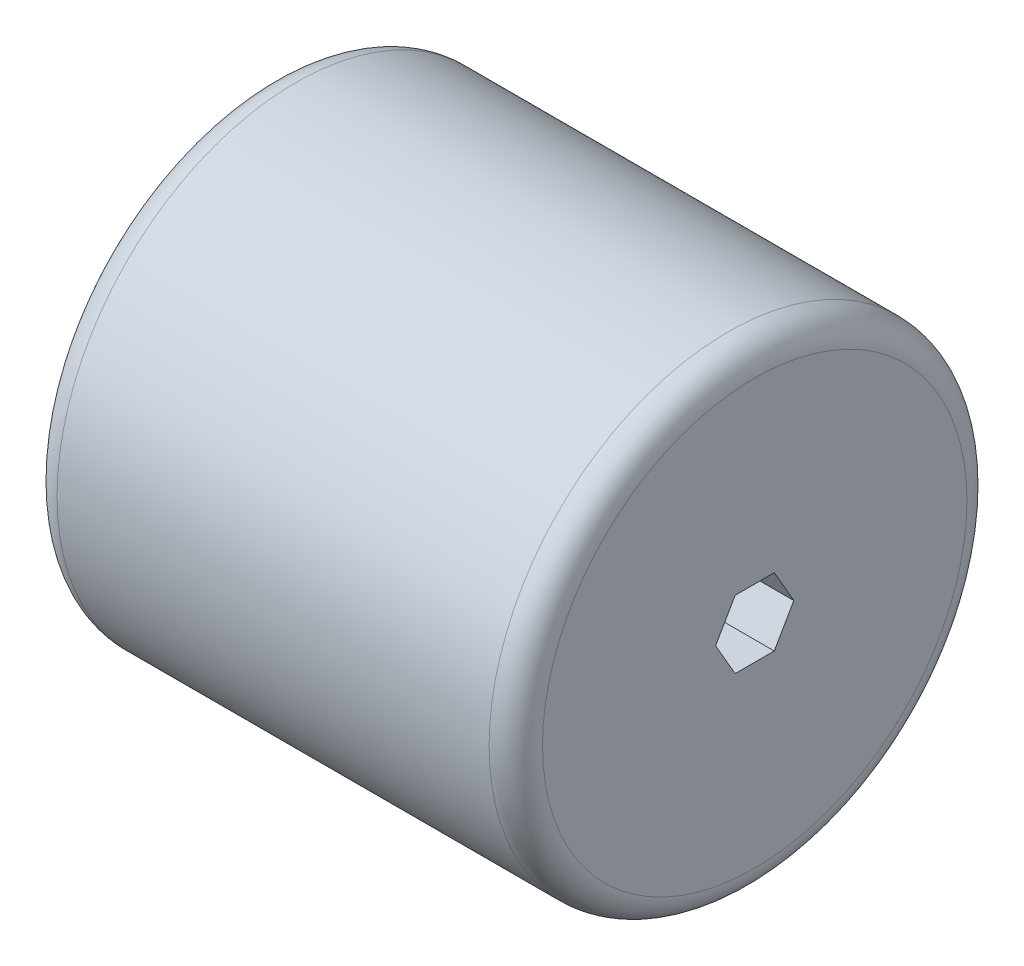
SolidWorks part; units mm, degrees
ref_plane "Alzado" through (0, 0, 0) normal (0, 0, 1) x (1, 0, 0)
ref_plane "Planta" through (0, 0, 0) normal (0, 1, 0) x (1, 0, 0)
ref_plane "Vista lateral" through (0, 0, 0) normal (1, 0, 0) x (0, 0, -1)
sketch "Croquis1" plane through (0, 0, 0) normal (1, 0, 0) x (0, 0, -1)
  line L1 (7.3323, 0) -> (3.6662, 6.35)
  line L2 (3.6662, 6.35) -> (-3.6662, 6.35)
  line L3 (-3.6662, 6.35) -> (-7.3323, 0)
  line L4 (-7.3323, 0) -> (-3.6662, -6.35)
  line L5 (-3.6662, -6.35) -> (3.6662, -6.35)
  line L6 (3.6662, -6.35) -> (7.3323, 0)
  circle A0 centre (0, 0) radius 6.35 construction
  circle A1 centre (0, 0) radius 44.77
  dimension "D2" = 89.54
  dimension "D1" = 12.7
extrude "Saliente-Extruir1" add sketch "Croquis1" along normal blind 90.96
fillet "Redondeo1" radius 5 2 edges at (0, 0, -44.77) (90.96, 0, -44.77)
